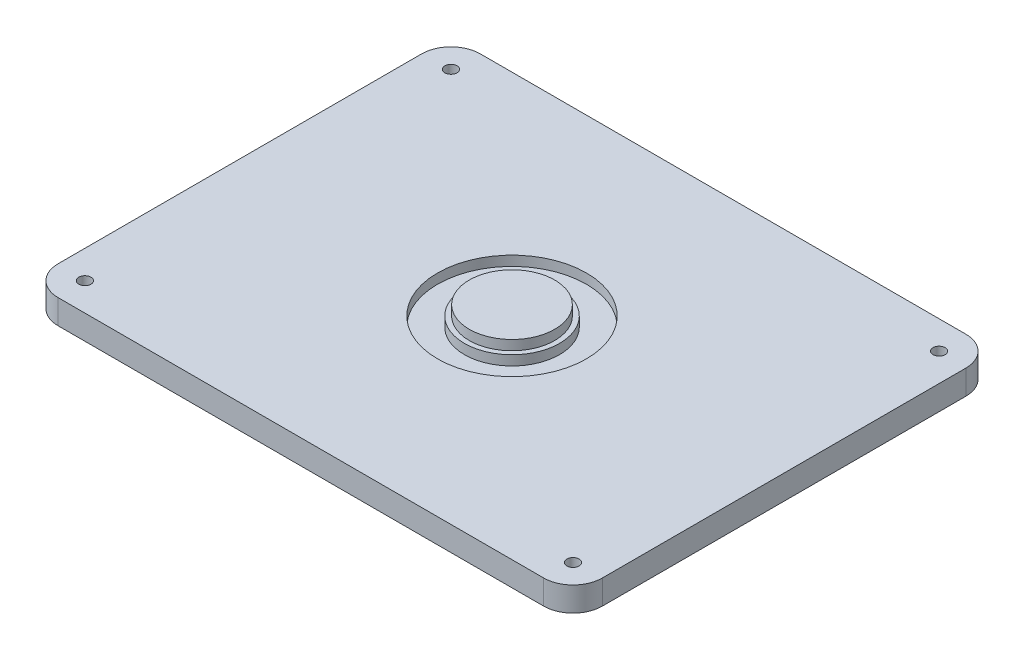
SolidWorks part; units mm, degrees
ref_plane "Front Plane" through (0, 0, 0) normal (0, 0, 1) x (1, 0, 0)
ref_plane "Top Plane" through (0, 0, 0) normal (0, 1, 0) x (1, 0, 0)
ref_plane "Right Plane" through (0, 0, 0) normal (1, 0, 0) x (0, 0, -1)
sketch "Sketch1" plane through (0, 0, 0) normal (0, 1, 0) x (1, 0, 0)
  line L1 (-100, 75) -> (100, 75) construction
  line L2 (-100, 75) -> (-100, -75) construction
  line L3 (-100, -75) -> (100, -75) construction
  line L4 (100, 75) -> (100, -75) construction
  line L5 (-100, 75) -> (100, -75) construction
  line L6 (-100, -75) -> (100, 75) construction
  line L7 (-99.5, 86.5) -> (99.5, 86.5)
  line L8 (-111.5, 74.5) -> (-111.5, -74.5)
  line L9 (-99.5, -86.5) -> (99.5, -86.5)
  line L10 (111.5, 74.5) -> (111.5, -74.5)
  line L11 (-111.5, 86.5) -> (111.5, -86.5) construction
  line L12 (-111.5, -86.5) -> (111.5, 86.5) construction
  circle A0 centre (100, 75) radius 2.5
  circle A1 centre (100, -75) radius 2.5
  circle A2 centre (-100, -75) radius 2.5
  circle A3 centre (-100, 75) radius 2.5
  arc A4 (99.5, -86.5) -> (111.5, -74.5) centre (99.5, -74.5) ccw
  arc A5 (-111.5, -74.5) -> (-99.5, -86.5) centre (-99.5, -74.5) ccw
  arc A6 (-99.5, 86.5) -> (-111.5, 74.5) centre (-99.5, 74.5) ccw
  arc A7 (99.5, 86.5) -> (111.5, 74.5) centre (99.5, 74.5) cw
  point P0 (0, 0)
  point P10 (0, 0)
  dimension "D3" = 5
  dimension "D4" = 5
  dimension "D5" = 5
  dimension "D6" = 5
  dimension "D9" = 12
  dimension "D1" = 150
  dimension "D2" = 200
  dimension "D7" = 173
  dimension "D8" = 223
extrude "Boss-Extrude1" add sketch "Sketch1" against normal blind 10
sketch "Sketch2" plane through (0, 0, 0) normal (0, 1, 0) x (1, 0, 0)
  circle A0 centre (0, 0) radius 30.5
  circle A1 centre (0, 0) radius 19.5
  dimension "D1" = 61
  dimension "D2" = 39
extrude "Cut-Extrude1" cut sketch "Sketch2" against normal blind 4
sketch "Sketch3" plane through (0, 0, 0) normal (0, 1, 0) x (1, 0, 0)
  circle A0 centre (0, 0) radius 17.5
  dimension "D1" = 35
extrude "Boss-Extrude2" add sketch "Sketch3" along normal blind 4
